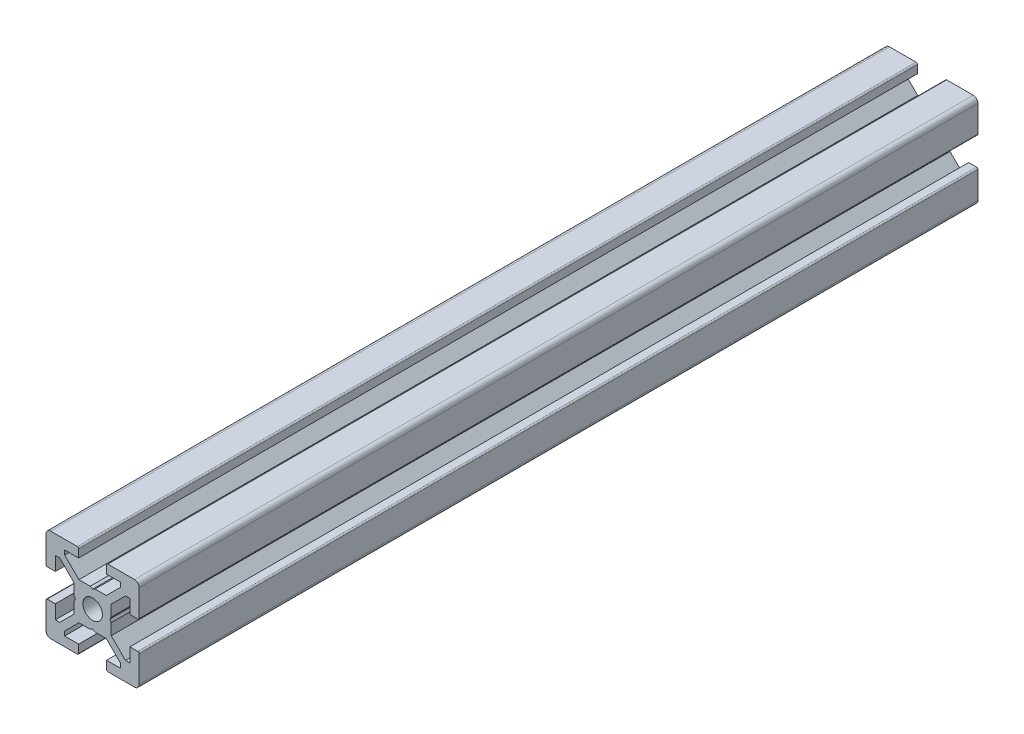
SolidWorks part; units mm, degrees
ref_plane "Front Plane" through (0, 0, 0) normal (0, 0, 1) x (1, 0, 0)
ref_plane "Top Plane" through (0, 0, 0) normal (0, 1, 0) x (1, 0, 0)
ref_plane "Right Plane" through (0, 0, 0) normal (1, 0, 0) x (0, 0, -1)
ref_plane "Plane1" through (0, 0, 0) normal (0, 0, 1) x (1, 0, 0)
sketch "Sketch1" plane through (0, 0, 0) normal (0, 0, 1) x (1, 0, 0)
  line L0 (-10, 9) -> (-10, 3.3)
  line L1 (-9.7, 3) -> (-8, 3)
  line L2 (-8, 3) -> (-8, 6)
  line L3 (-8, 6) -> (-7.0607, 6)
  line L4 (-7.0607, 6) -> (-4, 2.9393)
  line L5 (-4, 2.9393) -> (-4, 0.5196)
  line L6 (-4, 0.5196) -> (-3.7, 0)
  line L7 (-3.7, 0) -> (-4, -0.5196)
  line L8 (-4, -0.5196) -> (-4, -2.9393)
  line L9 (-4, -2.9393) -> (-7.0607, -6)
  line L10 (-7.0607, -6) -> (-8, -6)
  line L11 (-8, -6) -> (-8, -3)
  line L12 (-8, -3) -> (-9.7, -3)
  line L13 (-10, -3.3) -> (-10, -9)
  line L14 (-9, -10) -> (-3.3, -10)
  line L15 (-3, -9.7) -> (-3, -8)
  line L16 (-3, -8) -> (-6, -8)
  line L17 (-6, -8) -> (-6, -7.0607)
  line L18 (-6, -7.0607) -> (-2.9393, -4)
  line L19 (-2.9393, -4) -> (-0.5196, -4)
  line L20 (-0.5196, -4) -> (0, -3.7)
  line L21 (0, -3.7) -> (0.5196, -4)
  line L22 (0.5196, -4) -> (2.9393, -4)
  line L23 (2.9393, -4) -> (6, -7.0607)
  line L24 (6, -7.0607) -> (6, -8)
  line L25 (6, -8) -> (3, -8)
  line L26 (3, -8) -> (3, -9.7)
  line L27 (3.3, -10) -> (9, -10)
  line L28 (10, -9) -> (10, -3.3)
  line L29 (9.7, -3) -> (8, -3)
  line L30 (8, -3) -> (8, -6)
  line L31 (8, -6) -> (7.0606, -6)
  line L32 (7.0606, -6) -> (4, -2.9393)
  line L33 (4, -2.9393) -> (4, -0.5196)
  line L34 (4, -0.5196) -> (3.7, 0)
  line L35 (3.7, 0) -> (4, 0.5196)
  line L36 (4, 0.5196) -> (4, 2.9393)
  line L37 (4, 2.9393) -> (7.0607, 6)
  line L38 (7.0607, 6) -> (8, 6)
  line L39 (8, 6) -> (8, 3)
  line L40 (8, 3) -> (9.7, 3)
  line L41 (10, 3.3) -> (10, 9)
  line L42 (9, 10) -> (3.3, 10)
  line L43 (3, 9.7) -> (3, 8)
  line L44 (3, 8) -> (6, 8)
  line L45 (6, 8) -> (6, 7.0607)
  line L46 (6, 7.0607) -> (2.9393, 4)
  line L47 (2.9393, 4) -> (0.5196, 4)
  line L48 (0.5196, 4) -> (0, 3.7)
  line L49 (0, 3.7) -> (-0.5196, 4)
  line L50 (-0.5196, 4) -> (-2.9394, 4)
  line L51 (-2.9394, 4) -> (-6, 7.0606)
  line L52 (-6, 7.0606) -> (-6, 8)
  line L53 (-6, 8) -> (-3, 8)
  line L54 (-3, 8) -> (-3, 9.7)
  line L55 (-3.3, 10) -> (-9, 10)
  arc A0 (-10, 3.3) -> (-9.7, 3) centre (-9.7, 3.3) ccw
  arc A1 (-9.7, -3) -> (-10, -3.3) centre (-9.7, -3.3) ccw
  arc A2 (-10, -9) -> (-9, -10) centre (-9, -9) ccw
  arc A3 (-3.3, -10) -> (-3, -9.7) centre (-3.3, -9.7) ccw
  arc A4 (3, -9.7) -> (3.3, -10) centre (3.3, -9.7) ccw
  arc A5 (9, -10) -> (10, -9) centre (9, -9) ccw
  arc A6 (10, -3.3) -> (9.7, -3) centre (9.7, -3.3) ccw
  arc A7 (9.7, 3) -> (10, 3.3) centre (9.7, 3.3) ccw
  arc A8 (10, 9) -> (9, 10) centre (9, 9) ccw
  arc A9 (3.3, 10) -> (3, 9.7) centre (3.3, 9.7) ccw
  arc A10 (-3, 9.7) -> (-3.3, 10) centre (-3.3, 9.7) ccw
  arc A11 (-9, 10) -> (-10, 9) centre (-9, 9) ccw
extrude "Boss-Extrude1" add sketch "Sketch1" against normal blind 180
ref_plane "Plane2" through (0, 0, 0) normal (1, 0, 0) x (0, 0, -1)
sketch "Sketch2" plane through (0, 0, 0) normal (1, 0, 0) x (0, 0, -1)
  line L0 (0, 0) -> (0, 2.1)
  line L1 (0, 2.1) -> (400, 2.1)
  line L2 (400, 2.1) -> (400, 0)
  line L3 (400, 0) -> (0, 0)
  line L4 (400, 0) -> (0, 0) construction
revolve "Cut-Revolve1" cut sketch "Sketch2" angle 360 about L4
